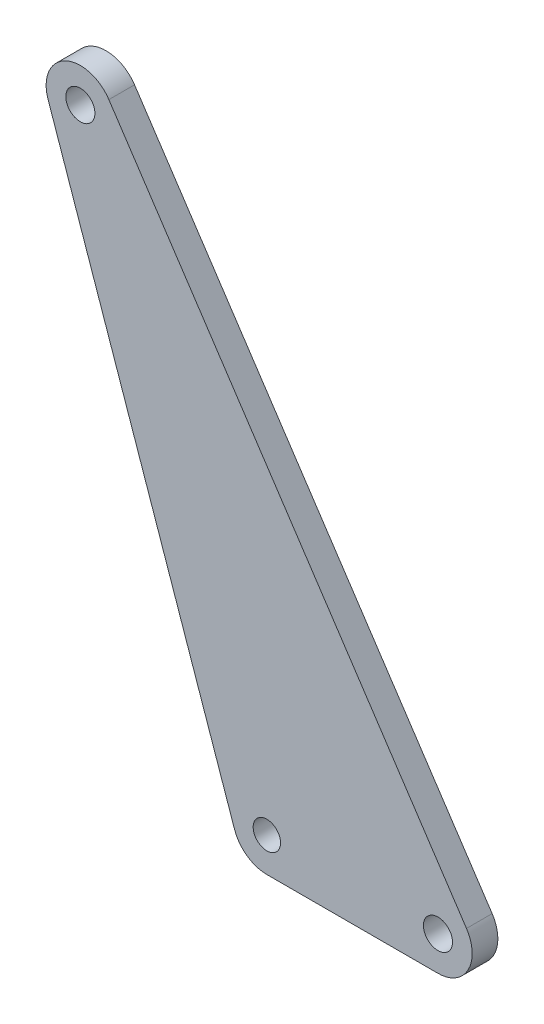
SolidWorks part; units mm, degrees
ref_plane "前视基准面" through (0, 0, 0) normal (0, 0, 1) x (1, 0, 0)
ref_plane "上视基准面" through (0, 0, 0) normal (0, 1, 0) x (1, 0, 0)
ref_plane "右视基准面" through (0, 0, 0) normal (1, 0, 0) x (0, 0, -1)
sketch "草图1" plane through (0, 0, 0) normal (0, 0, 1) x (1, 0, 0)
  line L0 (-22.4831, 4) -> (-2.4831, 4)
  line L1 (-22.4831, -4) -> (-2.4831, -4)
  line L2 (-22.4831, 0) -> (-44.2831, 0) construction
  line L4 (-44.2831, 0) -> (-44.2831, 63) construction
  line L5 (-48.0632, 61.692) -> (-26.2632, -1.308)
  line L7 (-40.95, 65.2115) -> (0.85, 2.2115)
  arc A4 (-22.4831, 4) -> (-22.4831, -4) centre (-22.4831, 0) ccw
  circle A5 centre (-22.4831, 0) radius 1.6
  arc A19 (-2.4831, 4) -> (-2.4831, -4) centre (-2.4831, 0) cw
  circle A20 centre (-2.4831, 0) radius 1.7
  circle A21 centre (-44.2831, 63) radius 1.7
  circle A22 centre (-44.2831, 63) radius 4
  point P22 (0, 0)
  dimension "D7" = 8
  dimension "D8" = 3.2
extrude "凸台-拉伸1" add sketch "草图1" along normal blind 3
